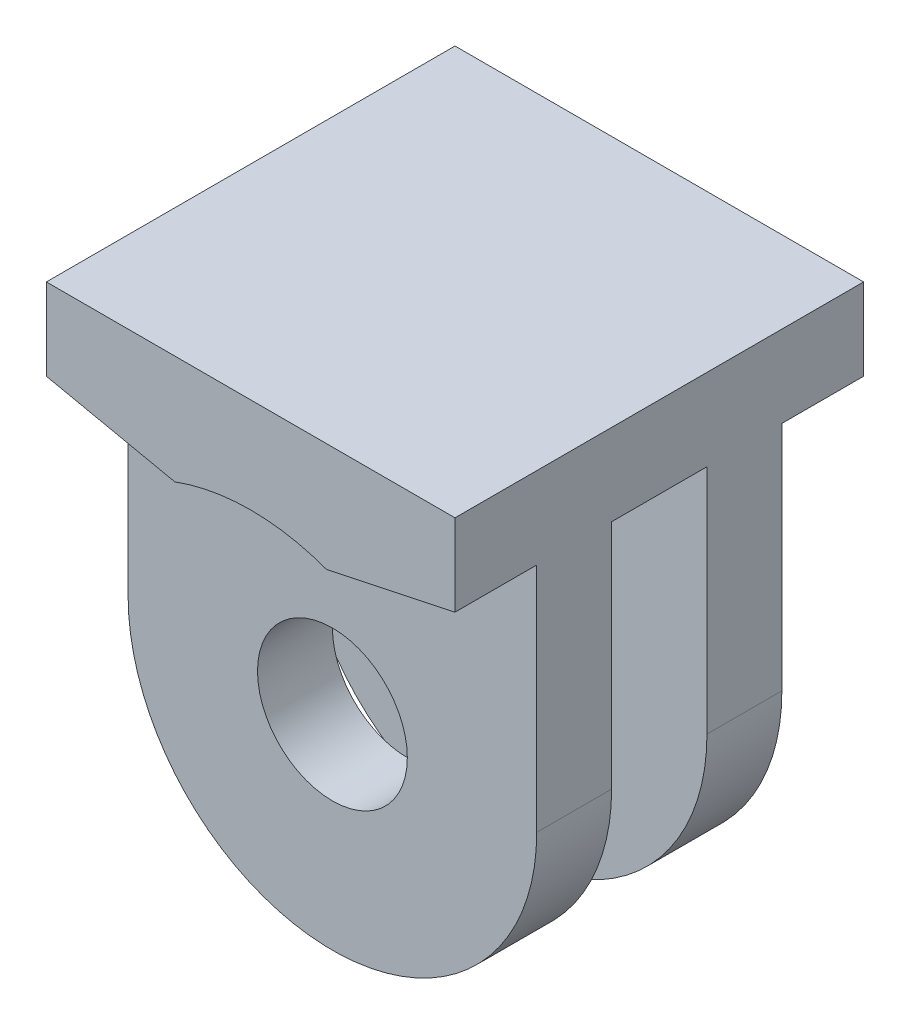
SolidWorks part; units mm, degrees
ref_plane "Front Plane" through (0, 0, 0) normal (0, 0, 1) x (1, 0, 0)
ref_plane "Top Plane" through (0, 0, 0) normal (0, 1, 0) x (1, 0, 0)
ref_plane "Right Plane" through (0, 0, 0) normal (1, 0, 0) x (0, 0, -1)
sketch "Sketch1" plane through (0, 0, 0) normal (0, 1, 0) x (1, 0, 0)
  line L1 (0, 0) -> (15, 0)
  line L2 (0, 0) -> (0, 7.5)
  line L3 (0, 7.5) -> (15, 7.5)
  line L4 (15, 0) -> (15, 7.5)
  dimension "D1" = 7.5
  dimension "D2" = 15
extrude "Boss-Extrude1" add sketch "Sketch1" along normal blind 4
sketch "Sketch3" plane through (0, 0, 0) normal (0, -1, 0) x (1, 0, 0)
  line L0 (0, -7.5) -> (0, 0) construction
  line L1 (0, -1.75) -> (15, -1.75)
  line L2 (0, -1.75) -> (0, -4.5)
  line L3 (0, -4.5) -> (15, -4.5)
  line L4 (15, -1.75) -> (15, -4.5)
  line L5 (15, 0) -> (15, -7.5) construction
  line L6 (0, 0) -> (15, 0) construction
  dimension "D1" = 1.75
  dimension "D2" = 4.5
extrude "Boss-Extrude3" add sketch "Sketch3" along normal blind 15
sketch "Sketch5" plane through (0, 0, -4.5) normal (0, 0, -1) x (-1, 0, 0)
  line L0 (-15, -15) -> (-15, 0) construction
  line L1 (0, -15) -> (0, 0) construction
  line L2 (0, -15) -> (-15, -15) construction
  line L3 (-15, -7.5) -> (-15, -17.342)
  line L4 (-15, -17.342) -> (0, -17.342)
  line L5 (0, -17.342) -> (0, -7.5)
  arc A0 (-15, -7.5) -> (0, -7.5) centre (-7.5, -7.5) ccw
extrude "Cut-Extrude2" cut sketch "Sketch5" against normal through all
sketch "Sketch6" plane through (0, 0, -7.5) normal (0, 0, -1) x (-1, 0, 0)
  line L0 (-15, 0) -> (0, 0) construction
  circle A1 centre (-7.5, -7.5) radius 2.75
  point P0 (0, 0)
  point P5 (-7.5, 0)
  dimension "D1" = 5.5
extrude "Cut-Extrude3" cut sketch "Sketch6" against normal through all
sketch "Sketch10" plane through (0, 0, -7.5) normal (0, 0, -1) x (-1, 0, 0)
  circle A0 centre (-7.5, -7.5) radius 8
  dimension "D1" = 16
extrude "Cut-Extrude6" cut sketch "Sketch10" against normal up to surface (3 mm away) up to face at (10.25, -7.5, -4.5)
sketch "Sketch13" plane through (0, 0, 0) normal (0, 0, 1) x (1, 0, 0)
  circle A0 centre (7.5, -7.5) radius 8
  dimension "D1" = 16
extrude "Cut-Extrude9" cut sketch "Sketch13" against normal up to surface (1.75 mm away) up to face at (4.75, -7.5, -1.75)
sketch "Sketch12" plane through (0, 0, -7.5) normal (0, 0, -1) x (-1, 0, 0)
  line L0 (-10.2839, 0) -> (-15, 1)
  line L1 (-15, 4) -> (-15, 0) construction
  line L2 (-15, 1) -> (-15, 0)
  line L3 (-15, 0) -> (-10.2839, 0)
  line L4 (-4.7161, 0) -> (0, 1)
  line L5 (0, 4) -> (0, 0) construction
  line L6 (0, 1) -> (0, 0)
  line L7 (0, 0) -> (-4.7161, 0)
  dimension "D1" = 1
extrude "Cut-Extrude8" cut sketch "Sketch12" against normal up to surface (3 mm away) up to face at (7.5, -3.6667, -4.5)
sketch "Sketch14" plane through (0, 0, 0) normal (0, 0, 1) x (1, 0, 0)
  line L0 (4.7161, 0) -> (0, 1)
  line L1 (0, 4) -> (0, 0) construction
  line L2 (0, 1) -> (0, 0)
  line L3 (0, 0) -> (4.7161, 0)
  line L4 (10.2839, 0) -> (15, 1)
  line L5 (15, 4) -> (15, 0) construction
  line L6 (15, 1) -> (15, 0)
  line L7 (15, 0) -> (10.2839, 0)
  dimension "D1" = 1
extrude "Cut-Extrude10" cut sketch "Sketch14" against normal up to surface (1.75 mm away) up to face at (7.5, -3.6667, -1.75)
mirror "Mirror1" about plane through (0, 4, 0) normal (0, 0, -1) of bodies 115 106
